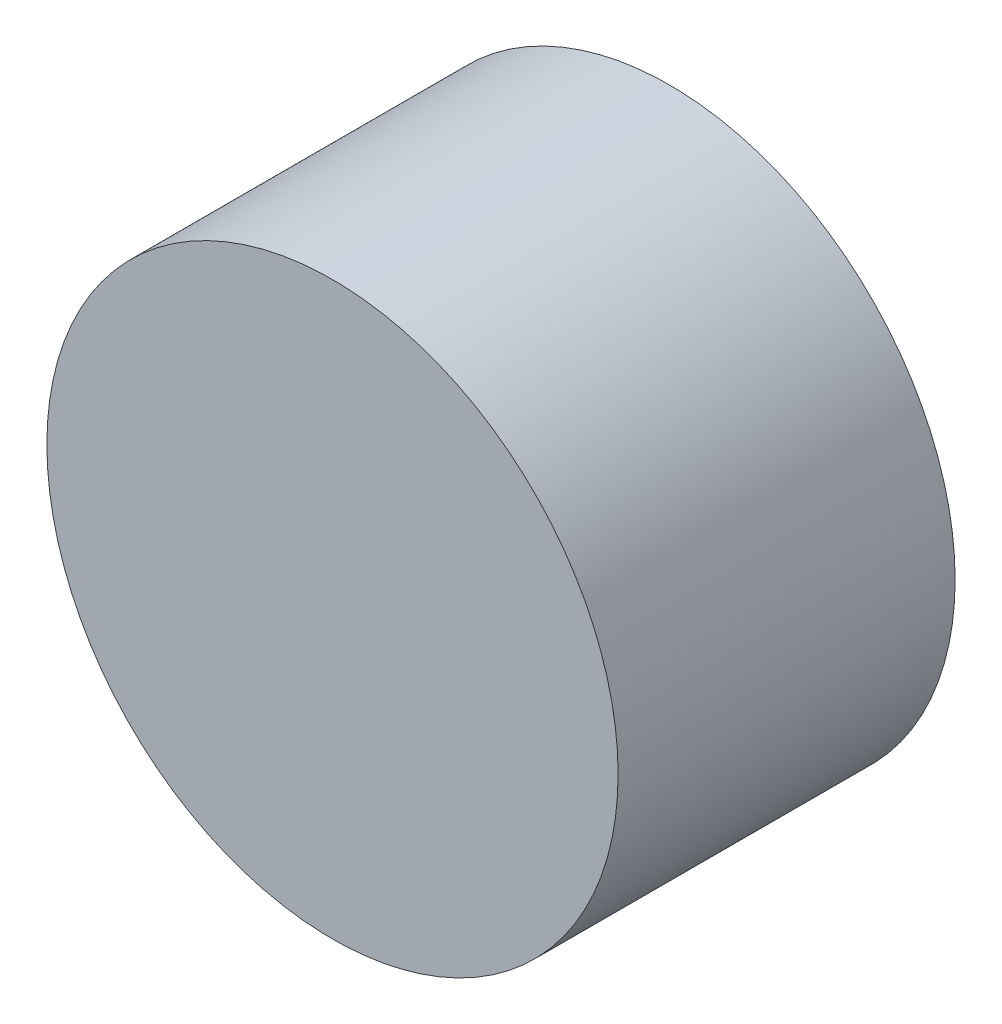
SolidWorks part; units mm, degrees
material "Malleable Cast Iron"
ref_plane "Front Plane" through (0, 0, 0) normal (0, 0, 1) x (1, 0, 0)
ref_plane "Top Plane" through (0, 0, 0) normal (0, 1, 0) x (1, 0, 0)
ref_plane "Right Plane" through (0, 0, 0) normal (1, 0, 0) x (0, 0, -1)
sketch "Sketch1" plane through (0, 0, 0) normal (0, 0, 1) x (1, 0, 0)
  circle A0 centre (0.1001, 0.1912) radius 16.95
  dimension "D1" = 33.9
extrude "Boss-Extrude1" add sketch "Sketch1" along normal blind 20
